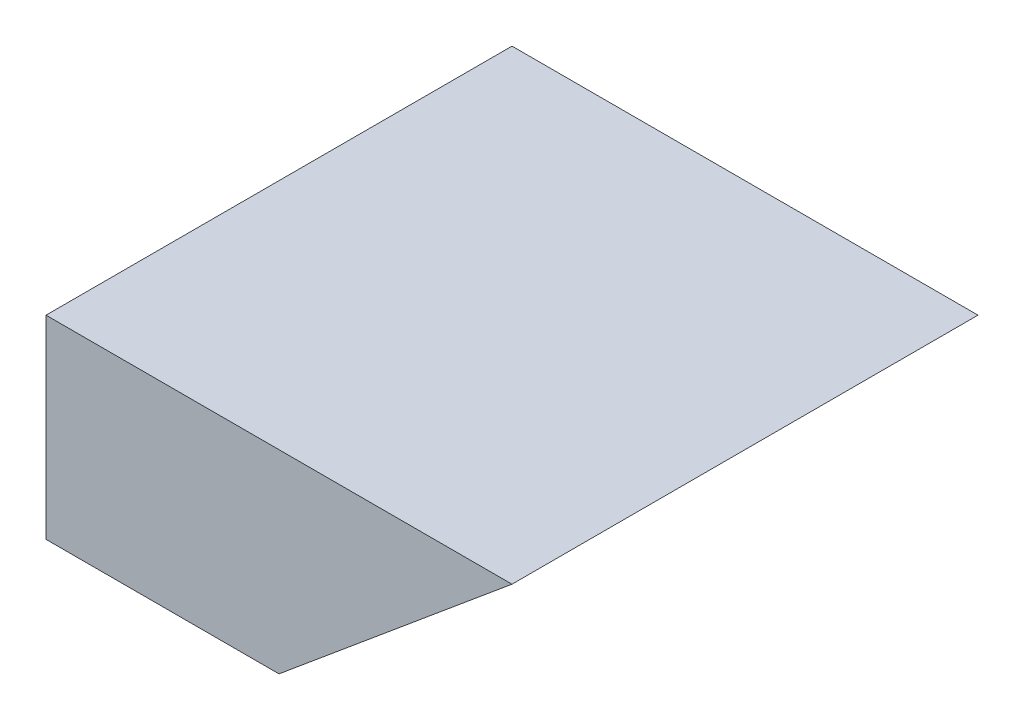
SolidWorks part; units mm, degrees
ref_plane "前视基准面" through (0, 0, 0) normal (0, 0, 1) x (1, 0, 0)
ref_plane "上视基准面" through (0, 0, 0) normal (0, 1, 0) x (1, 0, 0)
ref_plane "右视基准面" through (0, 0, 0) normal (1, 0, 0) x (0, 0, -1)
sketch "草图1" plane through (0, 0, 0) normal (0, 1, 0) x (1, 0, 0)
  line L1 (-60, 60) -> (60, 60)
  line L2 (-60, 60) -> (-60, -60)
  line L3 (-60, -60) -> (60, -60)
  line L4 (60, 60) -> (60, -60)
  line L5 (-60, 60) -> (60, -60) construction
  line L6 (-60, -60) -> (60, 60) construction
  point P0 (0, 0)
  dimension "D1" = 120
  dimension "D2" = 120
extrude "凸台-拉伸1" add sketch "草图1" along normal blind 50
sketch "草图2" plane through (0, 0, 60) normal (0, 0, 1) x (1, 0, 0)
  line L0 (60, 0) -> (0, 0)
  line L1 (-60, 0) -> (60, 0) construction
  line L2 (0, 0) -> (60, 50)
  line L3 (60, 50) -> (60, 0)
  dimension "D1" = 60
extrude "切除-拉伸1" cut sketch "草图2" against normal through all
sketch "草图3" plane through (0, 0, 0) normal (0.6402, -0.7682, 0) x (0.7682, 0.6402, 0)
  line L0 (0, 60) -> (0, 32.5)
  line L1 (0, -60) -> (0, 60) construction
  line L2 (0, 32.5) -> (35, 32.5)
  line L3 (35, 32.5) -> (35, -32.5)
  circle A0 centre (35, 32.5) radius 12.3519
  circle A1 centre (35, -32.5) radius 8.0474
  dimension "D1" = 27.5
  dimension "D2" = 35
  dimension "D3" = 65
